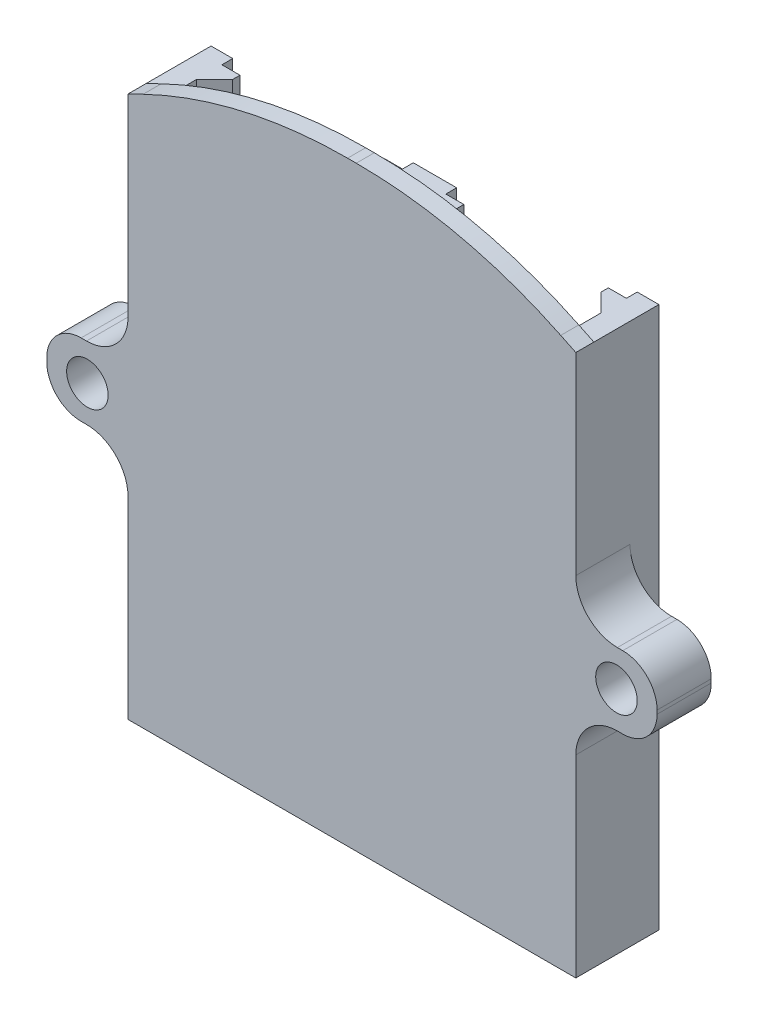
SolidWorks part; units mm, degrees
ref_plane "Přední rovina" through (0, 0, 0) normal (0, 0, 1) x (1, 0, 0)
ref_plane "Horní rovina" through (0, 0, 0) normal (0, 1, 0) x (1, 0, 0)
ref_plane "Pravá rovina" through (0, 0, 0) normal (1, 0, 0) x (0, 0, -1)
sketch "Skica1" plane through (0, 0, 0) normal (0, 1, 0) x (1, 0, 0)
  line L0 (-5, 0) -> (5, 0)
  line L1 (0, -1000) -> (0, 49000) construction
  line L2 (-5, 0) -> (-5, 1.6)
  line L3 (-5, 1.6) -> (-4, 2.6)
  line L4 (-4, 2.6) -> (-4, 3)
  line L6 (-6.2, 3.6) -> (-6.2, -1)
  line L7 (-6.2, -1) -> (6.2, -1)
  line L8 (0, -1) -> (0, 0) construction
  line L9 (-4, 3) -> (-5, 3)
  line L10 (-5, 3) -> (-5, 3.6)
  line L11 (-5, 3.6) -> (-6.2, 3.6)
  line L12 (5, 0) -> (5, 1.6)
  line L13 (5, 1.6) -> (4, 2.6)
  line L14 (4, 2.6) -> (4, 3)
  line L15 (4, 3) -> (5, 3)
  line L16 (5, 3) -> (5, 3.6)
  line L17 (6.2, 3.6) -> (6.2, -1)
  line L18 (5, 3.6) -> (6.2, 3.6)
  dimension "D2" = 0.4
  dimension "D1" = 5
  dimension "D3" = 1
  dimension "D4" = 1.2
  dimension "D5" = 1
  dimension "D6" = 1.6
  dimension "D7" = 1
  dimension "D8" = 0.6
extrude "Přidat vysunutím1" add sketch "Skica1" along normal blind 30
sketch "Skica2" plane through (0, 0, 0) normal (0, 0, 1) x (1, 0, 0)
  line L0 (-6.2, 30) -> (-6.2, 0) construction
  line L1 (-6.2, 19.3) -> (-6.2, 19.6)
  line L2 (-8.5, 13) -> (-8.8, 13)
  line L3 (-6.2, 13) -> (-6.2, 17)
  line L4 (-8.5, 17) -> (-8.8, 17)
  line L5 (-10.7, 14.9) -> (-10.7, 15.1)
  line L6 (-6.2, 10.7) -> (-6.2, 10.4)
  line L7 (-6.2, 19.6) -> (-6.2, 17)
  line L8 (-6.2, 10.4) -> (-6.2, 13)
  circle A0 centre (-8.45, 15) radius 1.15
  arc A1 (-8.8, 13) -> (-10.7, 14.9) centre (-8.8, 14.9) cw
  arc A2 (-10.7, 15.1) -> (-8.8, 17) centre (-8.8, 15.1) cw
  arc A3 (-8.5, 17) -> (-6.2, 19.3) centre (-8.5, 19.3) ccw
  arc A4 (-6.2, 10.7) -> (-8.5, 13) centre (-8.5, 10.7) ccw
  point P4 (-6.2, 15)
  dimension "D1" = 2.25
  dimension "D3" = 1.9
  dimension "D5" = 2.3
  dimension "D6" = 2.3
  dimension "D2" = 0
  dimension "D4" = 2
extrude "Přidat vysunutím2" add sketch "Skica2" along normal blind 1 and the other way blind 2 contours A4 L8 L3 L7 A3 L4 A2 L5 A1 L2 A0
sketch "Skica3" plane through (0, 0, 1) normal (0, 0, 1) x (1, 0, 0)
  line L0 (6.2, 30) -> (6.2, 0) construction
  line L1 (-6.2, 30) -> (6.2, 30)
  line L4 (6.2, 30) -> (6.2, 33)
  line L5 (-6.2, 30) -> (-5.3648, 30.4041)
  line L6 (5.9598, 33) -> (6.2, 33)
  arc A0 (-5.3648, 30.4041) -> (5.9598, 33) centre (5.9598, 7) cw
  dimension "D3" = 26
  dimension "D1" = 0
extrude "Přidat vysunutím3" add sketch "Skica3" against normal blind 1 contours L1 L4 L6 A0 L5
mirror "Zrcadlit2" about plane through (6.2, 30, -3.6) normal (-1, 0, 0) of "Přidat vysunutím3", "Přidat vysunutím2", "Přidat vysunutím1"
